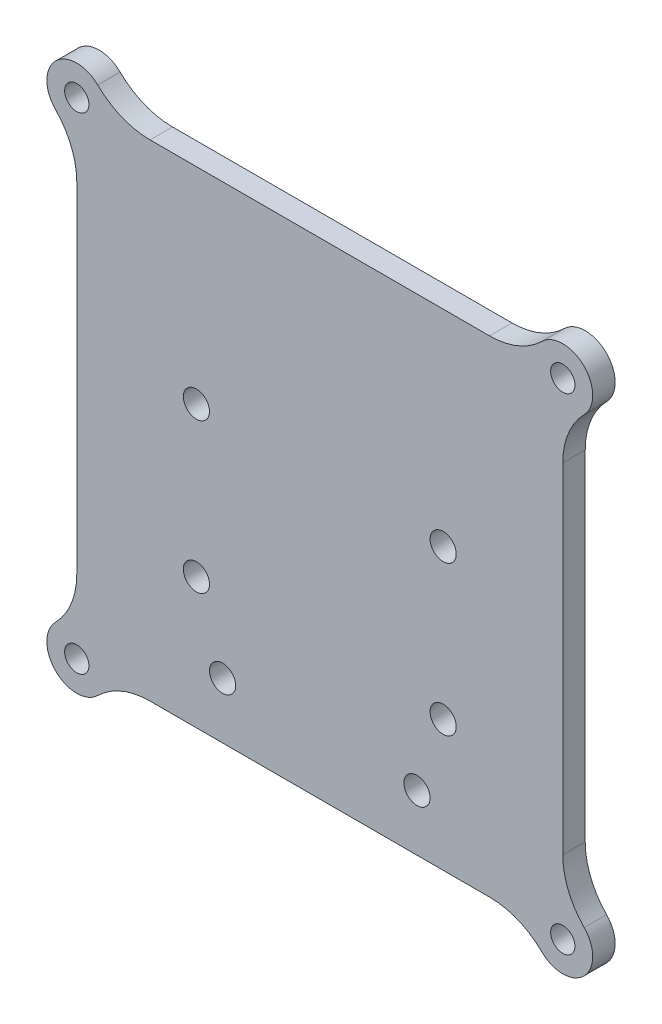
SolidWorks part; units mm, degrees
material "ABS"
ref_plane "Спереди" through (0, 0, 0) normal (0, 0, 1) x (1, 0, 0)
ref_plane "Сверху" through (0, 0, 0) normal (0, 1, 0) x (1, 0, 0)
ref_plane "Справа" through (0, 0, 0) normal (1, 0, 0) x (0, 0, -1)
sketch "Эскиз1" plane through (0, 0, 0) normal (0, 0, 1) x (1, 0, 0)
  line L1 (-32.5, -32.5) -> (32.5, -32.5)
  line L2 (-32.5, -32.5) -> (-32.5, 32.5)
  line L3 (-32.5, 32.5) -> (32.5, 32.5)
  line L4 (32.5, -32.5) -> (32.5, 32.5)
  line L5 (-32.5, -32.5) -> (32.5, 32.5) construction
  line L6 (-32.5, 32.5) -> (32.5, -32.5) construction
  circle A0 centre (-32.5, 32.5) radius 1.625
  arc A1 (-28.5, 32.5) -> (-32.5, 28.5) centre (-32.5, 32.5) ccw
  circle A2 centre (32.5, 32.5) radius 1.625
  arc A3 (32.5, 28.5) -> (28.5, 32.5) centre (32.5, 32.5) ccw
  circle A4 centre (32.5, -32.5) radius 1.625
  arc A5 (28.5, -32.5) -> (32.5, -28.5) centre (32.5, -32.5) ccw
  circle A6 centre (-32.5, -32.5) radius 1.625
  arc A7 (-32.5, -28.5) -> (-28.5, -32.5) centre (-32.5, -32.5) ccw
  point P0 (0, 0)
  point P20 (0, 0)
  dimension "D2" = 3.25
  dimension "D3" = 8
  dimension "D1" = 65
  dimension "D4" = 4
extrude "Бобышка-Вытянуть1" add sketch "Эскиз1" along normal blind 3 contours A6 L1 A4 L4 A2 L3 A0 L2 | L3 A1 L2 A0 | L4 A3 L3 A2 | L1 A5 L4 A4 | L2 A7 L1 A6
fillet "Скругление1" radius 10 8 edges at (-28.5, -32.5, 1.5) (-32.5, -28.5, 1.5) (-28.5, 32.5, 1.5) (-32.5, 28.5, 1.5) (28.5, 32.5, 1.5) (32.5, 28.5, 1.5) (32.5, -28.5, 1.5) (28.5, -32.5, 1.5)
sketch "Эскиз2" plane through (0, 0, 3) normal (0, 0, 1) x (1, 0, 0)
  line L0 (0, 32.5) -> (0, -32.5) construction
  line L1 (-22.702, 32.5) -> (22.702, 32.5) construction
  line L2 (-22.702, -32.5) -> (22.702, -32.5) construction
  line L3 (-15.6432, -25) -> (20.4381, -25) construction
  circle A0 centre (-13, -25) radius 1.75
  circle A1 centre (13, -25) radius 1.75
  dimension "D1" = 3.5
  dimension "D2" = 13
  dimension "D3" = 7.5
sketch "Эскиз3" plane through (0, 0, 3) normal (0, 0, 1) x (1, 0, 0)
  circle A0 centre (0, 0) radius 50
  dimension "D1" = 100
extrude "Вырез-Вытянуть1" cut sketch "Эскиз2" against normal blind 10
sketch "Эскиз4" plane through (0, 0, 3) normal (0, 0, 1) x (1, 0, 0)
  line L0 (0, -32.5) -> (0, 32.5) construction
  line L1 (-22.702, -32.5) -> (22.702, -32.5) construction
  line L2 (-22.702, 32.5) -> (22.702, 32.5) construction
  line L3 (-22.6055, -15) -> (24.9146, -15) construction
  circle A0 centre (-16.5, -15) radius 1.75
  circle A1 centre (16.5, -15) radius 1.75
  dimension "D1" = 3.5
  dimension "D2" = 16.5
  dimension "D3" = 17.5
extrude "Вырез-Вытянуть2" cut sketch "Эскиз4" against normal blind 10
sketch "Эскиз5" plane through (0, 0, 3) normal (0, 0, 1) x (1, 0, 0)
  line L0 (-32.5, 5) -> (32.5, 5) construction
  line L1 (-32.5, -22.702) -> (-32.5, 22.702) construction
  line L2 (32.5, -22.702) -> (32.5, 22.702) construction
  line L3 (0, -32.5) -> (0, 32.5) construction
  line L4 (-22.702, -32.5) -> (22.702, -32.5) construction
  line L5 (-22.702, 32.5) -> (22.702, 32.5) construction
  circle A0 centre (-16.5, 5) radius 1.75
  circle A1 centre (16.5, 5) radius 1.75
  dimension "D1" = 3.5
  dimension "D2" = 16.5
  dimension "D3" = 37.5
extrude "Вырез-Вытянуть3" cut sketch "Эскиз5" against normal blind 10
